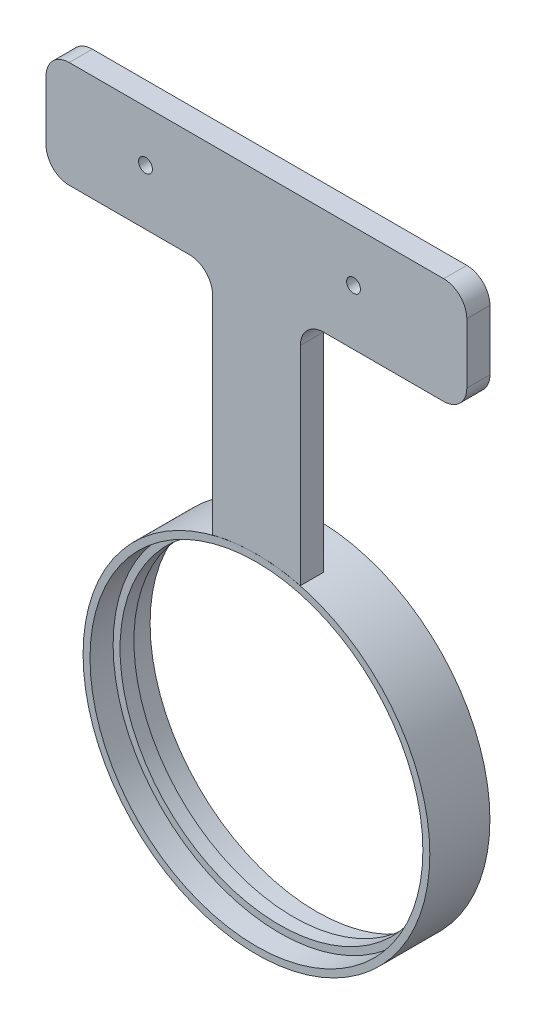
SolidWorks part; units mm, degrees
ref_plane "Plan de face" through (0, 0, 0) normal (0, 0, 1) x (1, 0, 0)
ref_plane "Plan de dessus" through (0, 0, 0) normal (0, 1, 0) x (1, 0, 0)
ref_plane "Plan de droite" through (0, 0, 0) normal (1, 0, 0) x (0, 0, -1)
sketch "Esquisse1" plane through (0, 0, 0) normal (0, 0, 1) x (1, 0, 0)
  line L1 (0, 0) -> (91, 0)
  line L2 (0, 0) -> (0, 73)
  line L3 (0, 73) -> (91, 73)
  line L4 (91, 0) -> (91, 73)
  dimension "D1" = 91
  dimension "D2" = 73
extrude "Boss.-Extru.1" add sketch "Esquisse1" along normal blind 5
sketch "Esquisse2" plane through (0, 0, 5) normal (0, 0, 1) x (1, 0, 0)
  line L0 (45.5, 73) -> (45.5, 0) construction
  line L1 (0, 0) -> (36, 0)
  line L2 (0, 0) -> (0, 50)
  line L3 (5, 50) -> (31, 50)
  line L4 (36, 0) -> (36, 45)
  line L5 (91, 73) -> (0, 73) construction
  line L6 (0, 0) -> (91, 0) construction
  line L7 (86, 50) -> (60, 50)
  line L8 (0, 55) -> (0, 50)
  line L9 (91, 55) -> (91, 50)
  line L10 (91, 0) -> (91, 50)
  line L11 (91, 0) -> (55, 0)
  line L12 (55, 0) -> (55, 45)
  arc A0 (31, 50) -> (36, 45) centre (31, 45) cw
  arc A1 (5, 50) -> (0, 55) centre (5, 55) cw
  arc A2 (60, 50) -> (55, 45) centre (60, 45) ccw
  arc A3 (86, 50) -> (91, 55) centre (86, 55) ccw
  dimension "D3" = 5
  dimension "D1" = 50
  dimension "D2" = 9.5
extrude "Enlèv. mat.-Extru.2" cut sketch "Esquisse2" against normal blind 10 contours L8 L2 L1 L4 A0 L3 A1 | A2 L12 L11 L10 L9 A3 L7
sketch "Esquisse3" plane through (0, 0, 5) normal (0, 0, 1) x (1, 0, 0)
  line L0 (45.5, 0) -> (45.5, -37.5) construction
  line L1 (36, 0) -> (55, 0) construction
  line L2 (36, 0) -> (55, 0)
  arc A0 (36, 0) -> (55, 0) centre (45.5, -37.5) cw
  dimension "D1" = 37.5
extrude "Enlèv. mat.-Extru.3" cut sketch "Esquisse3" against normal blind 10
sketch "Esquisse4" plane through (0, 0, 5) normal (0, 0, 1) x (1, 0, 0)
  line L0 (45.5, 1.1846) -> (45.5, -36.3154) construction
  arc A1 (55, 0) -> (36, 0) centre (45.5, -37.5) ccw construction
  circle A2 centre (45.5, -36.3154) radius 37.5
  dimension "D1" = 37.5
extrude "Boss.-Extru.2" add sketch "Esquisse4" against normal blind 13 separate body
sketch "Esquisse5" plane through (0, 0, 5) normal (0, 0, 1) x (1, 0, 0)
  line L0 (45.5, 1.1846) -> (45.5, -36.3154) construction
  circle A0 centre (45.5, -36.3154) radius 37.5 construction
  circle A1 centre (45.5, -36.3154) radius 36
extrude "Enlèv. mat.-Extru.4" cut sketch "Esquisse5" against normal blind 5
pattern_linear "Répétition linéaire1" count 2 spacing 8 along (0, 0, -1) of "Enlèv. mat.-Extru.4"
sketch "Esquisse6" plane through (0, 0, 0) normal (0, 0, 1) x (1, 0, 0)
  line L0 (45.5, -0.3154) -> (45.5, -36.3154) construction
  circle A0 centre (45.5, -36.3154) radius 36 construction
  circle A1 centre (45.5, -36.3154) radius 36 construction
  circle A2 centre (45.5, -36.3154) radius 34.5
extrude "Enlèv. mat.-Extru.5" cut sketch "Esquisse6" against normal blind 5
sketch "Esquisse7" plane through (0, 0, 5) normal (0, 0, 1) x (1, 0, 0)
  line L0 (91, 55) -> (91, 73) construction
  line L1 (5, 73) -> (86, 73)
  line L2 (0, 68) -> (0, 57.8263)
  line L3 (0, 57.8263) -> (91, 57.8263)
  line L4 (91, 68) -> (91, 57.8263)
  line L5 (0, 68) -> (0, 73)
  line L6 (0, 73) -> (5, 73)
  line L7 (45.5, 73) -> (45.5, 53.8915) construction
  line L8 (91, 68) -> (91, 73)
  line L9 (91, 73) -> (86, 73)
  arc A0 (91, 68) -> (86, 73) centre (86, 68) ccw
  arc A1 (5, 73) -> (0, 68) centre (5, 68) ccw
  arc A2 (86, 73) -> (91, 68) centre (86, 68) cw
  point P11 (0, 73)
  line M14 (91, 73) -> (0, 73)
  line M15 (0, 73) -> (0, 55)
  dimension "D1" = 5
extrude "Enlèv. mat.-Extru.6" cut sketch "Esquisse7" against normal blind 5 contours A1 M14 M15
fillet "Congé1" radius 5 1 edges at (91, 73, 2.5)
sketch "Esquisse8" plane through (0, 0, 5) normal (0, 0, 1) x (1, 0, 0)
  line L0 (0, 62) -> (91, 62) construction
  line L1 (0, 68) -> (0, 55) construction
  line L2 (91, 55) -> (91, 68) construction
  line L3 (86, 73) -> (5, 73) construction
  circle A0 centre (21.5, 62) radius 1.5
  circle A1 centre (66.5, 62) radius 1.5
  dimension "D1" = 11
  dimension "D2" = 24.5
  dimension "D3" = 45
extrude "Enlèv. mat.-Extru.7" cut sketch "Esquisse8" against normal blind 5
